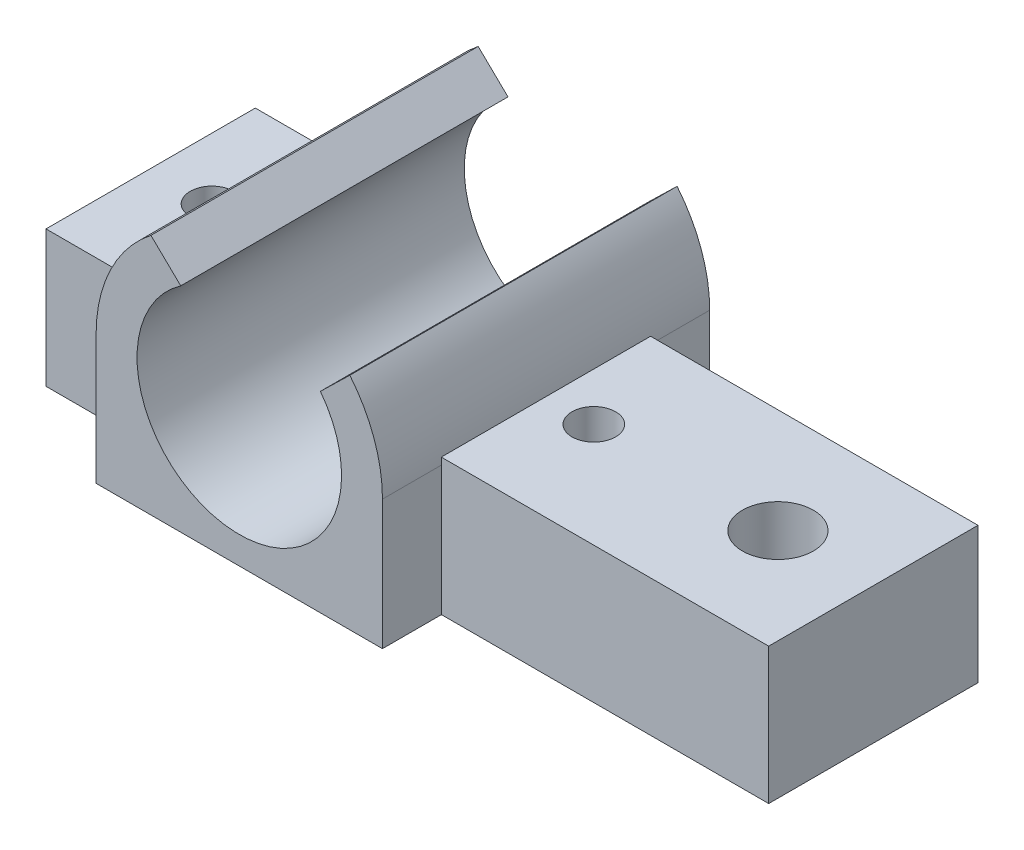
SolidWorks part; units mm, degrees
ref_plane "Front Plane" through (0, 0, 0) normal (0, 0, 1) x (1, 0, 0)
ref_plane "Top Plane" through (0, 0, 0) normal (0, 1, 0) x (1, 0, 0)
ref_plane "Right Plane" through (0, 0, 0) normal (1, 0, 0) x (0, 0, -1)
sketch "Sketch1" plane through (0, 0, 0) normal (0, 1, 0) x (1, 0, 0)
  line L0 (73.3937, 7.675) -> (73.3937, -7.675)
  line L1 (66.3937, 4.6765) -> (62.3437, 2.3383) construction
  line L2 (62.3437, 2.3383) -> (62.3437, -2.3383) construction
  line L3 (62.3437, -2.3383) -> (66.3937, -4.6765) construction
  line L4 (66.3937, -4.6765) -> (70.4437, -2.3383) construction
  line L5 (70.4437, -2.3383) -> (70.4437, 2.3383) construction
  line L6 (70.4437, 2.3383) -> (66.3937, 4.6765) construction
  line L7 (73.3937, -7.675) -> (20.3937, -7.675)
  line L9 (73.3937, 7.675) -> (20.3937, 7.675)
  line L10 (20.3937, -7.675) -> (20.3937, 7.675)
  line L11 (73.3937, -4.8412) -> (20.3937, 7.675) construction
  line L12 (73.3937, 4.8412) -> (20.3937, -7.675) construction
  circle A0 centre (52.8937, 0) radius 1.6
  circle A1 centre (24.8937, 0) radius 1.6
  circle A2 centre (66.3937, 0) radius 2.6
  circle A3 centre (66.3937, 0) radius 4.6765 construction
  dimension "D1" = 3.2
  dimension "D2" = 3.2
  dimension "D3" = 28
  dimension "D4" = 5.2
  dimension "D5" = 13.5
  dimension "D7" = 4.5
  dimension "D8" = 7
  dimension "D9" = 7.675
  dimension "D10" = 7.675
  dimension "D6" = 8.1
extrude "Boss-Extrude1" add sketch "Sketch1" along normal blind 10
sketch "Sketch2" plane through (0, 0, -7.675) normal (0, 0, -1) x (-1, 0, 0)
  line L3 (-23.2937, 10) -> (-26.4937, 10) construction
  line L4 (-23.2937, 10) -> (-26.4937, 10)
  line L5 (-24.8937, 10) -> (-24.8937, 21.3762)
  line L7 (-44.8413, 14.0691) -> (-47.0023, 16.171)
  line L8 (-34.5998, 15.6491) -> (-32.4128, 17.7612)
  line L12 (-49.3937, 0) -> (-28.3937, 0)
  line L13 (-28.3937, 9.5) -> (-28.3937, 0)
  line L15 (-49.3937, 9.5) -> (-49.3937, 0)
  arc A0 (-44.8413, 14.0691) -> (-34.5998, 15.6491) centre (-38.8937, 9.5) ccw
  arc A1 (-47.0023, 16.171) -> (-49.3937, 9.5) centre (-38.8937, 9.5) ccw
  arc A2 (-28.3937, 9.5) -> (-32.4128, 17.7612) centre (-38.8937, 9.5) ccw
  dimension "D1" = 15
  dimension "D2" = 14
  dimension "D4" = 21
extrude "Boss-Extrude2" add sketch "Sketch2" along normal blind 4.325 and the other way offset from surface (19.675 mm away) 4.325 contours A2 L8 A0 L7 A1 L15 L12 L13 other way up to face at (46.8937, 5, 7.675)
sketch "Sketch3" plane through (0, 0, 7.675) normal (0, 0, 1) x (1, 0, 0)
  line L1 (46.377, 10) -> (31.4104, 10)
  line L2 (46.377, 10) -> (31.4104, 10)
  arc A1 (31.4104, 10) -> (46.377, 10) centre (38.8937, 9.5) ccw
  arc A2 (31.4104, 10) -> (46.377, 10) centre (38.8937, 9.5) ccw
  dimension "D1" = 0
extrude "Cut-Extrude1" cut sketch "Sketch3" against normal through all
sketch "Sketch4" plane through (0, 0, 0) normal (0, -1, 0) x (1, 0, 0)
  line L1 (62.41, 2.3) -> (62.41, -2.3)
  line L2 (62.41, -2.3) -> (66.3937, -4.6)
  line L3 (66.3937, -4.6) -> (70.3775, -2.3)
  line L4 (70.3775, -2.3) -> (70.3775, 2.3)
  line L5 (70.3775, 2.3) -> (66.3937, 4.6)
  line L6 (66.3937, 4.6) -> (62.41, 2.3)
  circle A0 centre (66.3937, 0) radius 4.6 construction
  dimension "D1" = 9.2
extrude "Cut-Extrude2" cut sketch "Sketch4" against normal blind 4
sketch "Sketch5" plane through (0, 4, 0) normal (0, -1, 0) x (1, 0, 0)
  circle A0 centre (66.3937, 0) radius 2.6 construction
  circle A1 centre (66.3937, 0) radius 2.6
extrude "Boss-Extrude3" add sketch "Sketch5" against normal blind 0.4
